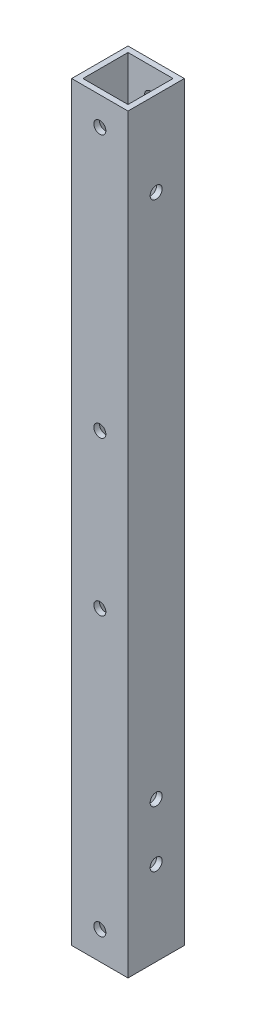
SolidWorks part; units mm, degrees
ref_plane "Front" through (0, 0, 0) normal (0, 0, 1) x (1, 0, 0)
ref_plane "Top" through (0, 0, 0) normal (0, 1, 0) x (1, 0, 0)
ref_plane "Right" through (0, 0, 0) normal (1, 0, 0) x (0, 0, -1)
sketch "ｽｹｯﾁ1" plane through (0, 0, 0) normal (0, 1, 0) x (1, 0, 0)
  line L0 (-6, 6) -> (6, 6)
  line L1 (-7.5, 7.5) -> (7.5, 7.5)
  line L2 (-7.5, 7.5) -> (-7.5, -7.5)
  line L3 (-7.5, -7.5) -> (7.5, -7.5)
  line L4 (7.5, 7.5) -> (7.5, -7.5)
  line L5 (0, -7.5) -> (0, 7.5) construction
  line L6 (-7.5, 0) -> (7.5, 0) construction
  line L7 (6, 6) -> (6, -6)
  line L8 (-6, -6) -> (6, -6)
  line L9 (-6, 6) -> (-6, -6)
  point P0 (0, 0)
  dimension "D1" = 15
  dimension "D2" = 15
  dimension "D3" = 1.5
extrude "ﾎﾞｽ - 押し出し1" add sketch "ｽｹｯﾁ1" along normal blind 200
sketch "ｽｹｯﾁ2" plane through (0, 0, 7.5) normal (0, 0, 1) x (1, 0, 0)
  line L0 (7.5, 200) -> (7.5, 0) construction
  line L1 (-7.5, 200) -> (7.5, 200) construction
  line L2 (-7.5, 0) -> (7.5, 0) construction
  line L3 (-7.5, 200) -> (-7.5, 0) construction
  circle A0 centre (0, 192.5) radius 1.6
  circle A1 centre (0, 7.5) radius 1.6
  circle A2 centre (0, 122.5) radius 1.6
  circle A3 centre (0, 81.5) radius 1.6
  dimension "D1" = 7.5
  dimension "D2" = 7.5
  dimension "D3" = 3.2
  dimension "D4" = 3.2
  dimension "D5" = 7.5
  dimension "D6" = 7.5
  dimension "D7" = 3.2
  dimension "D8" = 7.5
  dimension "D9" = 7.5
  dimension "D10" = 122.5
  dimension "D11" = 41
  dimension "D12" = 3.2
extrude "ｶｯﾄ - 押し出し1" cut sketch "ｽｹｯﾁ2" against normal through all
sketch "ｽｹｯﾁ3" plane through (7.5, 0, 0) normal (1, 0, 0) x (0, 0, -1)
  line L0 (-7.5, 0) -> (7.5, 0) construction
  line L1 (7.5, 200) -> (7.5, 0) construction
  line L2 (-7.5, 200) -> (7.5, 200) construction
  line L3 (-7.5, 200) -> (-7.5, 0) construction
  circle A0 centre (0, 177.5) radius 1.6
  circle A1 centre (0, 22.5) radius 1.6
  circle A2 centre (0, 37.5) radius 1.6
  dimension "D1" = 3.2
  dimension "D2" = 3.2
  dimension "D3" = 22.5
  dimension "D4" = 7.5
  dimension "D5" = 7.5
  dimension "D6" = 22.5
  dimension "D7" = 3.2
  dimension "D8" = 7.5
  dimension "D9" = 15
extrude "ｶｯﾄ - 押し出し2" cut sketch "ｽｹｯﾁ3" against normal through all
